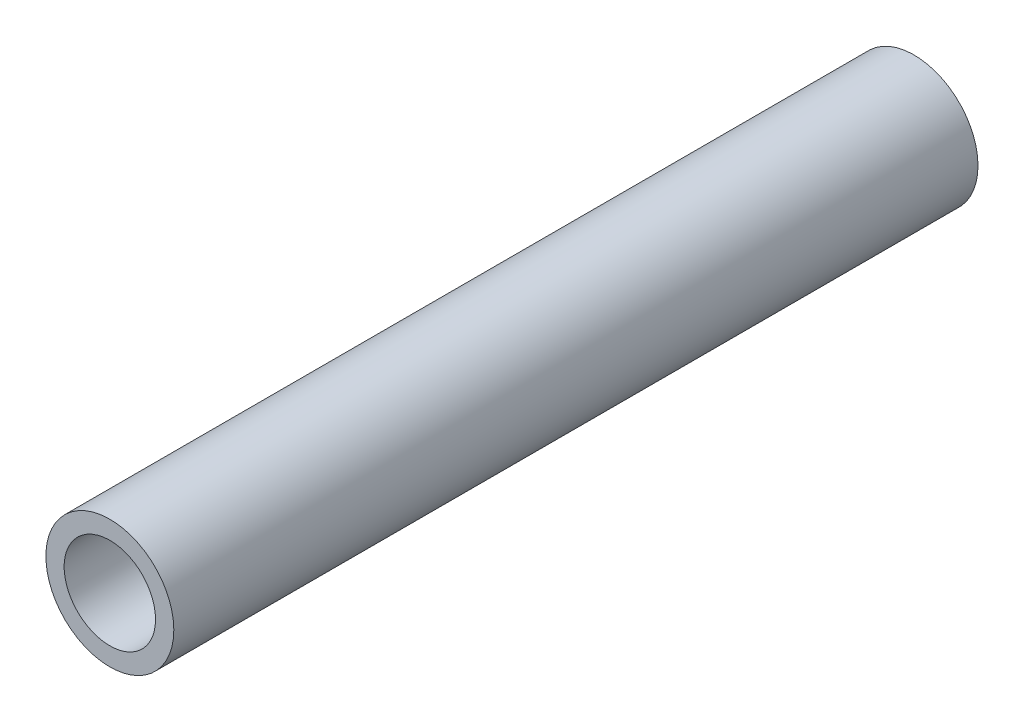
SolidWorks part; units mm, degrees
ref_plane "Front Plane" through (0, 0, 0) normal (0, 0, 1) x (1, 0, 0)
ref_plane "Top Plane" through (0, 0, 0) normal (0, 1, 0) x (1, 0, 0)
ref_plane "Right Plane" through (0, 0, 0) normal (1, 0, 0) x (0, 0, -1)
sketch "Sketch1" plane through (0, 0, 0) normal (0, 0, 1) x (1, 0, 0)
  circle A0 centre (0, 0) radius 7.9375
  circle A1 centre (0, 0) radius 11.1125
  dimension "D1" = 15.875
  dimension "D2" = 22.225
extrude "Boss-Extrude1" add sketch "Sketch1" against normal blind 139.7
